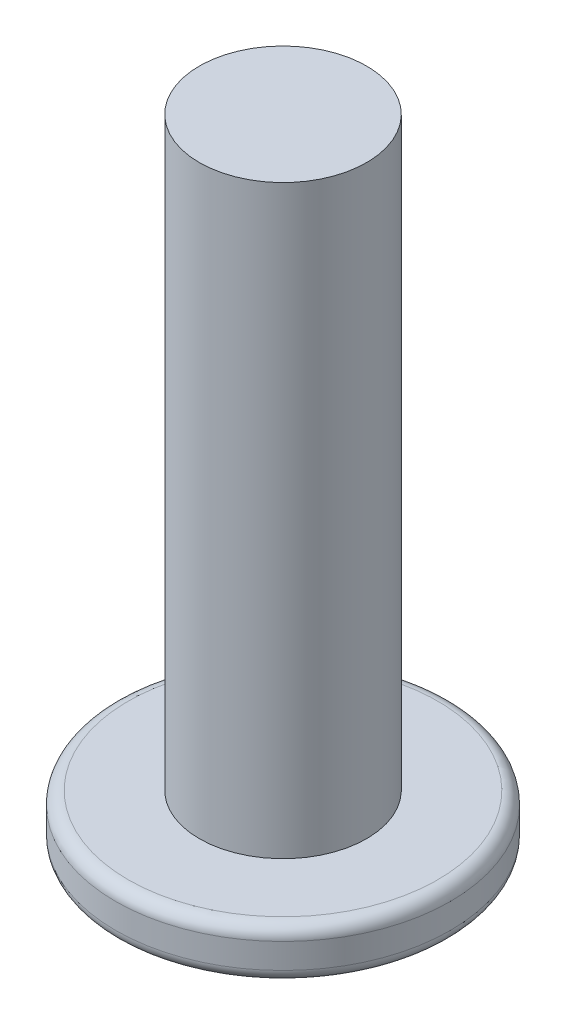
SolidWorks part; units mm, degrees
ref_plane "Front Plane" through (0, 0, 0) normal (0, 0, 1) x (1, 0, 0)
ref_plane "Top Plane" through (0, 0, 0) normal (0, 1, 0) x (1, 0, 0)
ref_plane "Right Plane" through (0, 0, 0) normal (1, 0, 0) x (0, 0, -1)
sketch "Sketch1" plane through (0, 0, 0) normal (0, 1, 0) x (1, 0, 0)
  circle A0 centre (0, 0) radius 4
  dimension "D1" = 8
extrude "Boss-Extrude1" add sketch "Sketch1" along normal blind 1.2
sketch "Sketch2" plane through (0, 1.2, 0) normal (0, 1, 0) x (1, 0, 0)
  circle A0 centre (0, 0) radius 2
  dimension "D1" = 4
extrude "Boss-Extrude2" add sketch "Sketch2" along normal blind 14
fillet "Fillet2" radius 0.3 2 edges at (0, 0, 4) (0, 1.2, 4)
sketch "Sketch3" plane through (0, 0, 0) normal (0, -1, 0) x (1, 0, 0)
  line L1 (1.7321, 0) -> (0.866, 1.5)
  line L2 (0.866, 1.5) -> (-0.866, 1.5)
  line L3 (-0.866, 1.5) -> (-1.7321, 0)
  line L4 (-1.7321, 0) -> (-0.866, -1.5)
  line L5 (-0.866, -1.5) -> (0.866, -1.5)
  line L6 (0.866, -1.5) -> (1.7321, 0)
  circle A0 centre (0, 0) radius 1.5 construction
  dimension "D1" = 3
extrude "Cut-Extrude1" cut sketch "Sketch3" against normal blind 0.6
